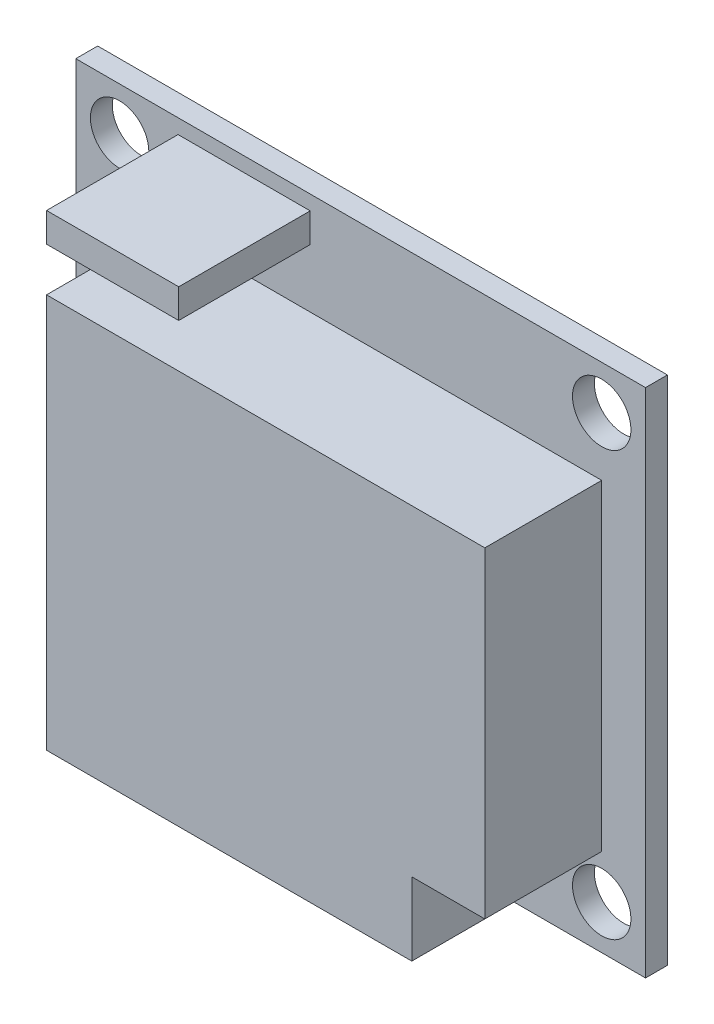
SolidWorks part; units mm, degrees
ref_plane "Plan de face" through (0, 0, 0) normal (0, 0, 1) x (1, 0, 0)
ref_plane "Plan de dessus" through (0, 0, 0) normal (0, 1, 0) x (1, 0, 0)
ref_plane "Plan de droite" through (0, 0, 0) normal (1, 0, 0) x (0, 0, -1)
sketch "Esquisse1" plane through (0, 0, 0) normal (0, 0, 1) x (1, 0, 0)
  line L1 (-19.5, -17.5) -> (19.5, -17.5)
  line L2 (-19.5, -17.5) -> (-19.5, 17.5)
  line L3 (-19.5, 17.5) -> (19.5, 17.5)
  line L4 (19.5, -17.5) -> (19.5, 17.5)
  line L5 (-19.5, -17.5) -> (19.5, 17.5) construction
  line L6 (-19.5, 17.5) -> (19.5, -17.5) construction
  point P0 (0, 0)
  dimension "D1" = 39
  dimension "D2" = 35
extrude "Boss.-Extru.1" add sketch "Esquisse1" along normal blind 1.5
sketch "Esquisse2" plane through (0, 0, 1.5) normal (0, 0, 1) x (1, 0, 0)
  line L0 (19.5, -17.5) -> (19.5, 17.5) construction
  line L1 (19.5, 17.5) -> (-19.5, 17.5) construction
  circle A0 centre (16.5, 14.5) radius 2
  dimension "D1" = 4
  dimension "D2" = 3
  dimension "D3" = 3
extrude "Enlèv. mat.-Extru.1" cut sketch "Esquisse2" against normal up to next contours A0
pattern_linear "Répétition linéaire1" count 2 spacing 33 along (-1, 0, 0) count 2 spacing 29 along (0, -1, 0) of "Enlèv. mat.-Extru.1"
sketch "Esquisse3" plane through (0, 0, 1.5) normal (0, 0, 1) x (1, 0, 0)
  line L0 (19.5, 17.5) -> (-19.5, 17.5) construction
  line L1 (-12.5, 16.5) -> (-3.4541, 16.5)
  line L2 (-12.5, 16.5) -> (-12.5, 14.5)
  line L3 (-12.5, 14.5) -> (-3.4541, 14.5)
  line L4 (-3.4541, 16.5) -> (-3.4541, 14.5)
  line L5 (-19.5, 17.5) -> (-19.5, -17.5) construction
  dimension "D1" = 1
  dimension "D2" = 7
  dimension "D3" = 2
extrude "Boss.-Extru.2" add sketch "Esquisse3" along normal blind 9
sketch "Esquisse4" plane through (0, 0, 1.5) normal (0, 0, 1) x (1, 0, 0)
  line L0 (-19.5, -17.5) -> (19.5, -17.5) construction
  line L1 (-13.5, 10.5) -> (16.5, 10.5)
  line L2 (-13.5, 10.5) -> (-13.5, -16.5)
  line L3 (-13.5, -16.5) -> (11.5, -16.5)
  line L4 (16.5, 10.5) -> (16.5, -11.5)
  line L5 (-19.5, 17.5) -> (-19.5, -17.5) construction
  line L6 (11.5, -16.5) -> (11.5, -11.5)
  line L7 (11.5, -11.5) -> (16.5, -11.5)
  dimension "D1" = 30
  dimension "D2" = 27
  dimension "D3" = 1
  dimension "D4" = 6
  dimension "D5" = 5
extrude "Boss.-Extru.3" add sketch "Esquisse4" along normal blind 8
